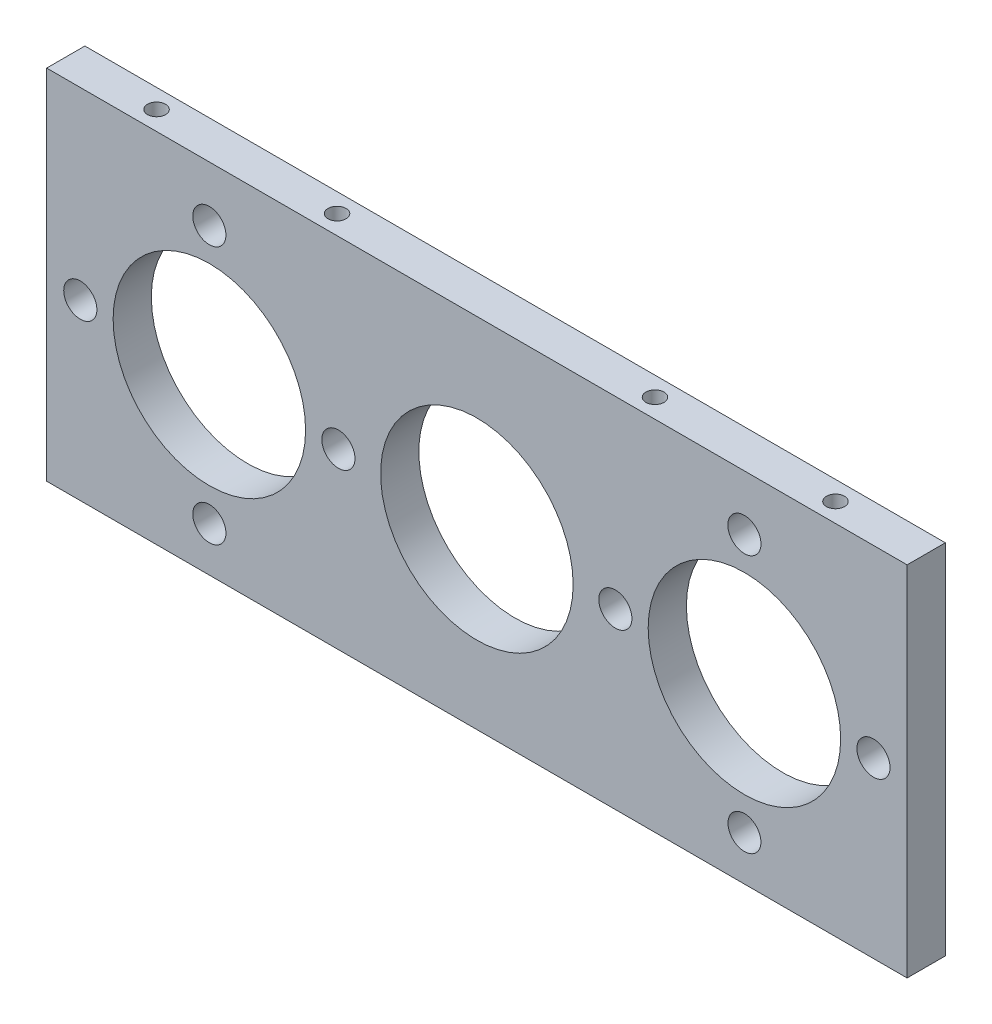
SolidWorks part; units mm, degrees
ref_plane "Plano frontal" through (0, 0, 0) normal (0, 0, 1) x (1, 0, 0)
ref_plane "Plano superior" through (0, 0, 0) normal (0, 1, 0) x (1, 0, 0)
ref_plane "Plano direito" through (0, 0, 0) normal (1, 0, 0) x (0, 0, -1)
sketch "Esboço1" plane through (0, 0, 0) normal (0, 0, 1) x (1, 0, 0)
  line L0 (71.505, 27.025) -> (-71.505, -27.025) construction
  line L1 (-71.505, 27.025) -> (71.505, 27.025)
  line L2 (-71.505, 27.025) -> (-71.505, -27.025)
  line L3 (-71.505, -27.025) -> (71.505, -27.025)
  line L4 (71.505, 27.025) -> (71.505, -27.025)
  dimension "D1" = 143.01
  dimension "D2" = 54.05
extrude "Ressalto-extrusão1" add sketch "Esboço1" along normal blind 6.35
sketch "Esboço2" plane through (0, 0, 0) normal (0, 0, -1) x (-1, 0, 0)
  circle A0 centre (-44.4631, 23.2919) radius 2.755
  circle A1 centre (-65.9131, 1.8419) radius 2.7556
  circle A2 centre (-44.4631, -19.6081) radius 2.7357
  circle A3 centre (-23.0131, 1.8419) radius 2.755
  circle A6 centre (23.0169, 1.8419) radius 2.755
  circle A9 centre (44.4669, -19.6081) radius 2.755
  circle A10 centre (65.9169, 1.8419) radius 2.755
  circle A11 centre (44.4669, 23.2919) radius 2.755
extrude "Corte-extrusão1" cut sketch "Esboço2" against normal up to surface (6.35 mm away) up to face at (0, 0, 6.35)
sketch "Esboço3" plane through (0, 0, 0) normal (0, 0, -1) x (-1, 0, 0)
  line L0 (71.505, 27.025) -> (71.505, -27.025) construction
  line L1 (-71.505, -27.025) -> (-71.505, 27.025) construction
  line L3 (71.505, -27.025) -> (-71.505, -27.025) construction
  circle A0 centre (-44.4631, 1.8419) radius 15.995
  circle A1 centre (0.0019, 1.8419) radius 10
  circle A2 centre (44.4669, 1.8419) radius 15.995
  dimension "D1" = 31.99
  dimension "D2" = 31.99
  dimension "D9" = 20
  dimension "D3" = 27.0381
  dimension "D4" = 27.0419
  dimension "D5" = 28.8669
  dimension "D6" = 28.8669
  dimension "D7" = 71.5069
  dimension "D8" = 28.8669
extrude "Corte-extrusão2" cut sketch "Esboço3" against normal blind 10
sketch "Esboço4" plane through (0, 0, 0) normal (0, 0, 1) x (1, 0, 0)
  line L1 (-71.505, 27.025) -> (71.505, 27.025)
  line L2 (-71.505, 27.025) -> (-71.505, 30.445)
  line L3 (-71.505, 30.445) -> (71.505, 30.445)
  line L4 (71.505, 27.025) -> (71.505, 30.445)
  dimension "D1" = 143.01
  dimension "D2" = 3.42
extrude "Ressalto-extrusão2" add sketch "Esboço4" along normal blind 6.35
sketch "Esboço5" plane through (0, 0, 6.35) normal (0, 0, 1) x (1, 0, 0)
  line L0 (-0.0019, 11.8419) -> (-0.0019, 1.8419) construction
  circle A0 centre (-0.0019, 1.8419) radius 10 construction
  circle A1 centre (-0.0019, 1.8419) radius 16
  dimension "D1" = 32
extrude "Corte-extrusão3" cut sketch "Esboço5" against normal blind 10
sketch "Croquis1" plane through (0, 0, 6.35) normal (0, 0, 1) x (1, 0, 0)
  line L0 (-71.505, 30.445) -> (-71.505, -27.025) construction
  line L1 (-71.505, 30.445) -> (71.505, 30.445)
  line L2 (-71.505, 30.445) -> (-71.505, 32.445)
  line L3 (-71.505, 32.445) -> (71.505, 32.445)
  line L4 (71.505, 30.445) -> (71.505, 32.445)
  line L5 (71.505, -27.025) -> (71.505, 30.445) construction
  dimension "D1" = 2
extrude "Saliente-Extruir2" add sketch "Croquis1" against normal blind 6.35
sketch "Esboço6" plane through (0, 32.445, 0) normal (0, 1, 0) x (1, 0, 0)
  line L0 (71.505, -3.175) -> (-71.505, -3.175) construction
  line L3 (0, 0) -> (0, -3.175) construction
  line L5 (71.505, -3.175) -> (-71.5868, -3.175) construction
  line L6 (0, -0.1516) -> (0, -7.1516) construction
  circle A0 centre (56.4232, -3.175) radius 1.5
  circle A1 centre (26.4232, -3.175) radius 1.5
  circle A2 centre (-26.4232, -3.175) radius 1.5
  circle A3 centre (-56.4232, -3.175) radius 1.5
  dimension "D1" = 3
  dimension "D2" = 3
extrude "Corte-extrusão4" cut sketch "Esboço6" against normal blind 17
